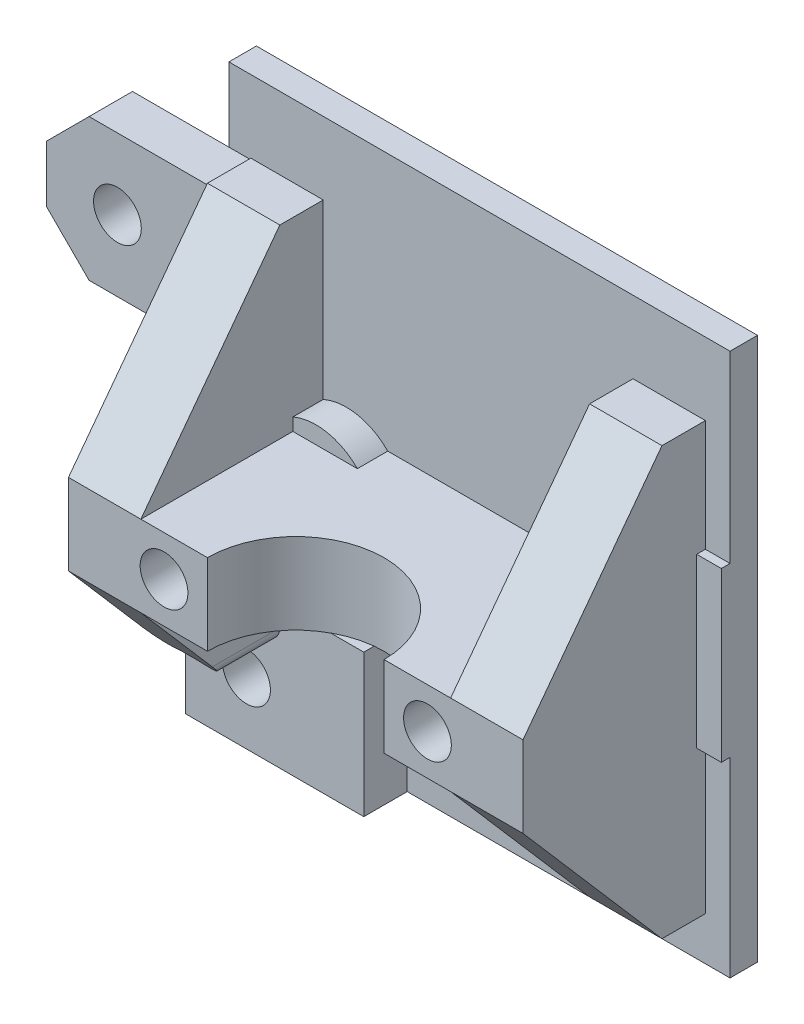
SolidWorks part; units mm, degrees
ref_plane "前视基准面" through (0, 0, 0) normal (0, 0, 1) x (1, 0, 0)
ref_plane "上视基准面" through (0, 0, 0) normal (0, 1, 0) x (1, 0, 0)
ref_plane "右视基准面" through (0, 0, 0) normal (1, 0, 0) x (0, 0, -1)
other "Configuration Table"
sketch "Sketch2" plane through (0, -22.0888, 0) normal (0, -1, 0) x (1, 0, 0)
  line L1 (7.5815, 14.5) -> (2.5815, 14.5)
  line L3 (2.5815, 14.5) -> (0.9815, 14.5)
  line L4 (0.9815, 14.5) -> (0.9815, 0)
  line L5 (0.9815, 0) -> (26.3815, 0)
  line L6 (26.3815, 0) -> (26.3815, 14.5)
  line L7 (26.3815, 14.5) -> (24.7815, 14.5)
  line L9 (24.7815, 14.5) -> (19.7815, 14.5)
  circle A2 centre (13.6815, 14.5) radius 6.1
  arc A3 (7.5815, 14.5) -> (19.7815, 14.5) centre (13.6815, 14.5) ccw
  dimension "D2" = 5
  dimension "D3" = 5
  dimension "D4" = 1.6
  dimension "D5" = 1.6
  dimension "D1" = 0.1
extrude "Boss-Extrude1" add sketch "Sketch2" along normal offset from surface (5.6 mm away) 0.2 from offset 0.2
sketch "Sketch4" plane through (0, 0, 0) normal (0, 0, 1) x (1, 0, 0)
  line L61 (5.7815, -39.6388) -> (5.7815, -41.9888)
  line L64 (31.0815, -4.4888) -> (-3.5371, -4.4888)
  line L65 (5.7815, -39.6388) -> (5.7815, -36.3474)
  line L66 (5.7815, -36.3474) -> (2.7229, -33.2888)
  line L67 (2.7229, -33.2888) -> (-3.5371, -33.2888)
  line L68 (-3.5371, -33.2888) -> (-3.5371, -4.4888)
  line L69 (5.7815, -39.6388) -> (5.7815, -36.3474)
  line L70 (5.7815, -36.3474) -> (2.7229, -33.2888)
  line L71 (2.7229, -33.2888) -> (-3.5371, -33.2888)
  line L72 (-3.5371, -33.2888) -> (-3.5371, -4.4888)
  line L73 (31.0815, -4.4888) -> (31.0815, -41.9888)
  line L74 (31.0815, -4.4888) -> (31.0815, -41.9888)
  line L75 (31.0815, -41.9888) -> (5.7815, -41.9888)
  point P3 (0, 0)
  dimension "D2" = 0.1
  dimension "D1" = 0.1
extrude "Boss-Extrude2" add sketch "Sketch4" along normal offset from surface (1.9 mm away) 0.2
sketch "Sketch5" plane through (0, 0, 1.9) normal (0, 0, 1) x (1, 0, 0)
  line L0 (5.7815, -36.3474) -> (5.7815, -41.9888) construction
  line L19 (-3.7371, -19.3888) -> (-3.7371, -9.5888)
  line L20 (-3.7371, -9.5888) -> (-10.1957, -9.5888)
  line L21 (-10.1957, -9.5888) -> (-13.1371, -12.5302)
  line L22 (-13.1371, -12.5302) -> (-13.1371, -16.4474)
  line L23 (-13.1371, -16.4474) -> (-10.1957, -19.3888)
  line L24 (-10.1957, -19.3888) -> (-3.7371, -19.3888)
  line L26 (-3.7371, -9.5888) -> (-10.1957, -9.5888)
  line L27 (-10.1957, -9.5888) -> (-13.1371, -12.5302)
  line L28 (-13.1371, -12.5302) -> (-13.1371, -16.4474)
  line L29 (-13.1371, -16.4474) -> (-10.1957, -19.3888)
  line L30 (-10.1957, -19.3888) -> (-3.7371, -19.3888)
  line L31 (-3.7371, -9.5888) -> (-0.5371, -9.5888)
  line L32 (-0.5371, -9.5888) -> (-0.5371, -19.3888)
  line L33 (-0.5371, -19.3888) -> (-3.7371, -19.3888)
  line L34 (5.7815, -41.9888) -> (-3.5371, -41.9888)
  line L35 (-3.5371, -33.4888) -> (-3.5371, -32.1433)
  line L36 (-3.5371, -4.4888) -> (-3.5371, -33.2888) construction
  line L37 (2.6401, -42.5388) -> (5.5815, -39.5974)
  line L38 (5.5815, -39.5974) -> (5.5815, -36.4302)
  line L39 (5.5815, -36.4302) -> (2.6401, -33.4888)
  line L40 (2.6401, -33.4888) -> (-3.5371, -33.4888)
  line L41 (-3.5371, -33.4888) -> (-3.5371, -42.5388)
  line L42 (-3.5371, -42.5388) -> (2.6401, -42.5388)
  line L47 (-3.5371, -33.4888) -> (-3.5371, -41.9888)
  line L49 (-3.5371, -32.1433) -> (8.7815, -32.1433)
  line L50 (8.7815, -32.1433) -> (8.7815, -41.9888)
  line L51 (5.7815, -41.9888) -> (31.0815, -41.9888) construction
  line L52 (8.7815, -41.9888) -> (5.7815, -41.9888)
  circle A0 centre (0.6815, -37.6388) radius 1.65
  circle A1 centre (-8.2371, -14.4888) radius 1.65
  dimension "D3" = 3
  dimension "D5" = 3.3
  dimension "D6" = 3.3
  dimension "D4" = 3
  dimension "D1" = 0.1
  dimension "D2" = 0.1
extrude "Boss-Extrude3" add sketch "Sketch5" along normal blind 3
sketch "Sketch6" plane through (0, 0, 1.9) normal (0, 0, 1) x (1, 0, 0)
  line L8 (31.0815, -41.9888) -> (31.0815, -4.4888) construction
  line L10 (26.3815, -27.7888) -> (31.1815, -27.7888) construction
  line L11 (31.0815, -28.7888) -> (25.3815, -28.7888)
  line L12 (31.0815, -28.7888) -> (31.0815, -17.1888)
  line L13 (31.0815, -17.1888) -> (25.3815, -17.1888)
  line L14 (25.3815, -28.7888) -> (25.3815, -17.1888)
  line L15 (26.3815, -18.1888) -> (31.1815, -18.1888) construction
  line L16 (26.3815, -27.7888) -> (26.3815, -18.1888) construction
  dimension "D1" = 1
  dimension "D2" = 1
  dimension "D3" = 1
extrude "Boss-Extrude4" add sketch "Sketch6" along normal up to surface (0.6 mm away)
ref_plane "Plane1" through (13.6815, 0, 0) normal (1, 0, 0) x (0, 0, -1)
sketch "Sketch9" plane through (26.3815, 0, 0) normal (1, 0, 0) x (0, 0, -1)
  line L0 (-1.9, -38.9888) -> (-4.9, -38.9888)
  line L1 (-1.9, -41.9888) -> (-1.9, -28.7888) construction
  line L2 (-4.9, -38.9888) -> (-14.5, -27.8888)
  line L3 (-14.5, -27.8888) -> (-14.5, -22.2888)
  line L4 (-14.5, -22.2888) -> (-4.9, -9.4888)
  line L5 (-4.9, -9.4888) -> (-1.9, -9.4888)
  line L6 (-1.9, -17.1888) -> (-1.9, -4.4888) construction
  line L7 (-1.9, -9.4888) -> (-1.9, -38.9888)
  line L8 (-1.9, -41.9888) -> (0, -41.9888) construction
  line L9 (-1.9, -4.4888) -> (0, -4.4888) construction
  point P4 (0, 0)
  dimension "D1" = 3
  dimension "D2" = 5
  dimension "D3" = 3
  dimension "D4" = 3
extrude "Boss-Extrude5" add sketch "Sketch9" along normal blind 3 and the other way blind 2
sketch "Sketch3" plane through (0, 0, 14.5) normal (0, 0, 1) x (1, 0, 0)
  line L1 (19.7815, -27.8888) -> (19.7815, -22.2888) construction
  line L3 (24.3815, -22.2888) -> (19.7815, -22.2888) construction
  circle A0 centre (22.7815, -25.0888) radius 1.65
  dimension "D1" = 3.3
  dimension "D2" = 3
  dimension "D3" = 2.8
extrude "Cut-Extrude1" cut sketch "Sketch3" against normal blind 50
sketch "Sketch10" plane through (0, 0, 0) normal (0, 0, -1) x (-1, 0, 0)
  circle A0 centre (-22.7815, -25.0888) radius 4
  circle A1 centre (-22.7815, -25.0888) radius 1.65
  dimension "D1" = 8
extrude "Boss-Extrude6" add sketch "Sketch10" against normal blind 4
sketch "Sketch11" plane through (0, 0, 0) normal (0, 0, -1) x (-1, 0, 0)
  line L1 (-22.7815, -21.9134) -> (-25.5315, -23.5011)
  line L2 (-25.5315, -23.5011) -> (-25.5315, -26.6765)
  line L3 (-25.5315, -26.6765) -> (-22.7815, -28.2642)
  line L4 (-22.7815, -28.2642) -> (-20.0315, -26.6765)
  line L5 (-20.0315, -26.6765) -> (-20.0315, -23.5011)
  line L6 (-20.0315, -23.5011) -> (-22.7815, -21.9134)
  circle A0 centre (-22.7815, -25.0888) radius 2.75 construction
  dimension "D1" = 5.5
extrude "Cut-Extrude3" cut sketch "Sketch11" against normal blind 3
mirror "Mirror1" about plane through (13.6815, 0, 0) normal (1, 0, 0) of "Cut-Extrude3", "Boss-Extrude6", "Cut-Extrude1", "Boss-Extrude5"
sketch "Sketch13" plane through (0, 0, 1.9) normal (0, 0, -1) x (-1, 0, 0)
  circle A0 centre (-0.6815, -37.6388) radius 1.65
extrude "Cut-Extrude4" cut sketch "Sketch13" against normal blind 10
sketch "Sketch14" plane through (0, 0, 4.9) normal (0, 0, 1) x (1, 0, 0)
  circle A0 centre (0.6815, -37.6388) radius 3.25
  dimension "D1" = 6.5
extrude "Cut-Extrude5" cut sketch "Sketch14" along normal blind 10
fillet "Fillet1" radius 1 2 edges at (2.9815, -35.3426, 6.4767) (-2.0185, -35.8298, 6.2661)
